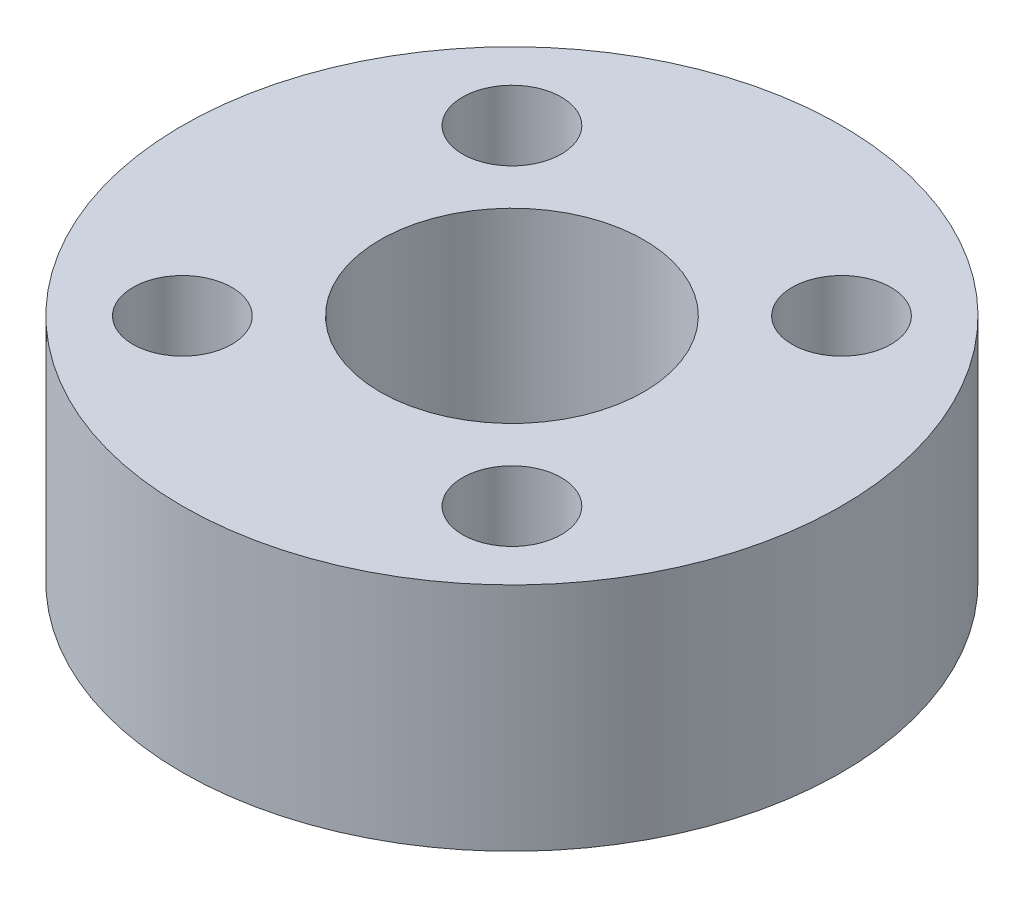
SolidWorks part; units mm, degrees
ref_plane "前视基准面" through (0, 0, 0) normal (0, 0, 1) x (1, 0, 0)
ref_plane "上视基准面" through (0, 0, 0) normal (0, 1, 0) x (1, 0, 0)
ref_plane "右视基准面" through (0, 0, 0) normal (1, 0, 0) x (0, 0, -1)
other "Configuration Table"
sketch "草图1" plane through (0, 0, 0) normal (0, 1, 0) x (1, 0, 0)
  circle A0 centre (0, 0) radius 10
  dimension "D1" = 20
extrude "凸台-拉伸1" add sketch "草图1" along normal blind 7
sketch "草图2" plane through (0, 7, 0) normal (0, 1, 0) x (1, 0, 0)
  line L1 (-5, -5) -> (5, -5)
  line L2 (-5, -5) -> (-5, 5)
  line L3 (-5, 5) -> (5, 5)
  line L4 (5, -5) -> (5, 5)
  line L5 (-5, -5) -> (5, 5) construction
  line L6 (-5, 5) -> (5, -5) construction
  circle A0 centre (0, 0) radius 4
  circle A1 centre (-5, 5) radius 1.5
  circle A2 centre (-5, -5) radius 1.5
  circle A3 centre (5, -5) radius 1.5
  circle A4 centre (5, 5) radius 1.5
  dimension "D1" = 8
  dimension "D4" = 3
  dimension "D5" = 3
  dimension "D6" = 3
  dimension "D7" = 3
  dimension "D2" = 10
  dimension "D3" = 10
extrude "切除-拉伸1" cut sketch "草图2" against normal blind 7 contours A0 | A1 | A2 | A3 | A4
